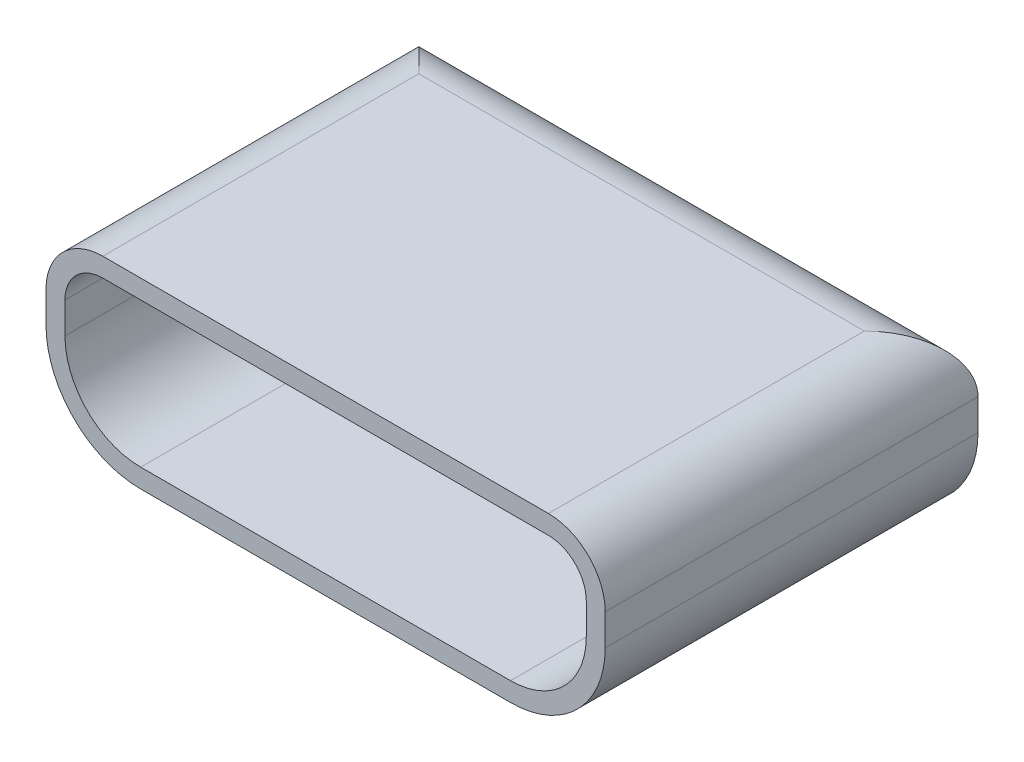
SolidWorks part; units mm, degrees
ref_plane "Front Plane" through (0, 0, 0) normal (0, 0, 1) x (1, 0, 0)
ref_plane "Top Plane" through (0, 0, 0) normal (0, 1, 0) x (1, 0, 0)
ref_plane "Right Plane" through (0, 0, 0) normal (1, 0, 0) x (0, 0, -1)
sketch "Sketch1" plane through (0, 0, 0) normal (0, 0, 1) x (1, 0, 0)
  line L1 (3.75, -1.225) -> (-3.75, -1.225)
  line L2 (3.75, -1.225) -> (3.75, 1.225)
  line L3 (3.75, 1.225) -> (-3.75, 1.225)
  line L4 (-3.75, -1.225) -> (-3.75, 1.225)
  line L5 (3.75, -1.225) -> (-3.75, 1.225) construction
  line L6 (3.75, 1.225) -> (-3.75, -1.225) construction
  point P0 (0, 0)
  dimension "D1" = 2.45
  dimension "D2" = 7.5
extrude "Boss-Extrude1" add sketch "Sketch1" along normal blind 5
fillet "Fillet1" radius 0.762 3 edges at (-3.75, 1.225, 2.5) (0, 1.225, 0) (3.75, 1.225, 2.5)
fillet "Fillet2" radius 1.27 2 edges at (-3.75, -1.225, 2.5) (3.75, -1.225, 2.5)
sketch "Sketch2" plane through (0, 0, 5) normal (0, 0, 1) x (1, 0, 0)
  line L24 (3.496, 0.045) -> (3.496, 0.463)
  line L25 (-2.48, -0.971) -> (2.48, -0.971)
  line L26 (-3.496, 0.463) -> (-3.496, 0.045)
  line L27 (2.988, 0.971) -> (-2.988, 0.971)
  line L28 (3.496, 0.045) -> (3.496, 0.463)
  line L29 (-2.48, -0.971) -> (2.48, -0.971)
  line L30 (-3.496, 0.463) -> (-3.496, 0.045)
  line L31 (2.988, 0.971) -> (-2.988, 0.971)
  arc A20 (3.496, 0.463) -> (2.988, 0.971) centre (2.988, 0.463) ccw
  arc A21 (2.48, -0.971) -> (3.496, 0.045) centre (2.48, 0.045) ccw
  arc A22 (-3.496, 0.045) -> (-2.48, -0.971) centre (-2.48, 0.045) ccw
  arc A23 (-2.988, 0.971) -> (-3.496, 0.463) centre (-2.988, 0.463) ccw
  arc A24 (3.496, 0.463) -> (2.988, 0.971) centre (2.988, 0.463) ccw
  arc A25 (2.48, -0.971) -> (3.496, 0.045) centre (2.48, 0.045) ccw
  arc A26 (-3.496, 0.045) -> (-2.48, -0.971) centre (-2.48, 0.045) ccw
  arc A27 (-2.988, 0.971) -> (-3.496, 0.463) centre (-2.988, 0.463) ccw
  dimension "D1" = 0.254
extrude "Cut-Extrude1" cut sketch "Sketch2" against normal blind 4
